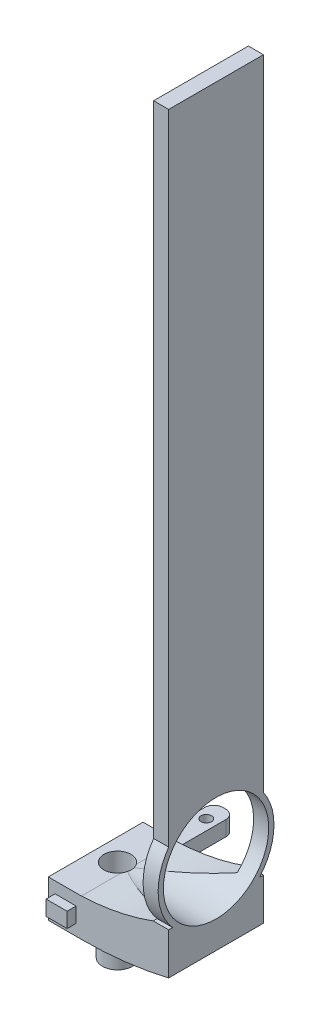
SolidWorks part; units mm, degrees
material "Cast Alloy Steel"
ref_plane "Front Plane" through (0, 0, 0) normal (0, 0, 1) x (1, 0, 0)
ref_plane "Top Plane" through (0, 0, 0) normal (0, 1, 0) x (1, 0, 0)
ref_plane "Right Plane" through (0, 0, 0) normal (1, 0, 0) x (0, 0, -1)
sketch "Sketch1" plane through (0, 0, 0) normal (0, 0, 1) x (1, 0, 0)
  line L0 (0, 0) -> (0, 25.0004)
  line L1 (0, 25.0004) -> (22, 25.0004)
  line L3 (22, 0) -> (0, 0)
  line L4 (0, 25.0004) -> (0, -234) construction
  line L8 (80, 38.7514) -> (80, 6.7987)
  arc A0 (22, 25.0004) -> (80, 38.7514) centre (15.9028, 179.9111) ccw
  arc A1 (22, 0) -> (80, 6.7987) centre (22, 250.8008) ccw
  dimension "D1" = 22
  dimension "D2" = 80
  dimension "D3" = 22
extrude "Boss-Extrude1" add sketch "Sketch1" along normal blind 48
sketch "Sketch2" plane through (0, 0, 48) normal (0, 0, 1) x (1, 0, 0)
  line L0 (0, 0) -> (0, 7.5) construction
  line L1 (0, 25.0004) -> (0, 0) construction
  line L2 (0, 7.5) -> (4.5, 7.5) construction
  line L3 (4.5, 7.5) -> (4.5, 17.5)
  line L4 (4.5, 17.5) -> (18.5, 17.5)
  line L5 (18.5, 17.5) -> (18.5, 7.5)
  line L6 (4.5, 7.5) -> (18.5, 7.5)
  dimension "D1" = 14
  dimension "D2" = 10
  dimension "D3" = 4.5
extrude "Boss-Extrude2" add sketch "Sketch2" along normal blind 50
ref_plane "Plane1" through (0, 0, 24) normal (0, 0, 1) x (1, 0, 0)
sketch "Sketch4" plane through (0, 17.5, 0) normal (0, 1, 0) x (1, 0, 0)
  line L0 (11.5, -48) -> (11.5, -86)
  line L1 (18.5, -48) -> (4.5, -48) construction
hole_wizard "M8x1.0 Tapped Hole1" positions "3DSketch1" profile "Sketch5" tap size "M8x1.0" standard "ANSI Metric"
sketch3d "3DSketch1"
  point P0 (11.5, 17.5, 86)
sketch "Sketch5" plane through (11.5, 17.5, 86) normal (1, 0, 0) x (0, 0, 1)
  line L0 (0, 0) -> (0, 12.103)
  line L1 (0, 12.103) -> (3.5, 10)
  line L2 (3.5, 10) -> (3.5, 0)
  line L5 (3.5, 0) -> (0, 0)
  line L10 (0, 12.103) -> (-3.5, 10) construction
  line L11 (0, -6.35) -> (0, 107.95) construction
  dimension "Tap Drill Dia." = 7
  dimension "Tap Drill Depth" = 10
  dimension "Drill Angle" = 118
cosmetic thread "Hole Thread1" parameters "D1"=10, "D2"=8
fillet "Fillet1" radius 6 2 edges at (4.5, 12.5, 98) (18.5, 12.5, 98)
ref_plane "Plane2" through (80, 0, 0) normal (-1, 0, 0) x (0, 0, 1)
sketch "Sketch7" plane through (80, 0, 0) normal (-1, 0, 0) x (0, 0, 1)
  line L0 (24, 25.0004) -> (24, 60.0004) construction
  line L1 (48, 25.0004) -> (0, 25.0004) construction
  circle A0 centre (24, 60.0004) radius 35
  circle A1 centre (24, 60.0004) radius 38.5
extrude "Boss-Extrude3" add sketch "Sketch7" along normal blind 10
sketch "Sketch8" plane through (80, 0, 0) normal (-1, 0, 0) x (0, 0, 1)
  circle A0 centre (24, 60.0004) radius 35
extrude "Cut-Extrude2" cut sketch "Sketch8" along normal blind 90
sketch "Sketch10" plane through (0, 0, 0) normal (0, -1, 0) x (1, 0, 0)
  line L0 (0, 24) -> (14.5, 24) construction
  line L1 (0, 48) -> (0, 0) construction
  circle A0 centre (14.5, 24) radius 12
  circle A1 centre (14.5, 24) radius 9
extrude "Boss-Extrude4" add sketch "Sketch10" along normal blind 5 and the other way blind 10
sketch "Sketch11" plane through (0, -5, 0) normal (0, -1, 0) x (1, 0, 0)
  circle A0 centre (14.5, 24) radius 10
  circle A1 centre (14.5, 24) radius 9
extrude "Boss-Extrude5" add sketch "Sketch11" along normal blind 25
sketch "Sketch12" plane through (0, 0, 0) normal (0, -1, 0) x (-1, 0, 0)
  circle A0 centre (-14.5, -24) radius 9
extrude "Cut-Extrude3" cut sketch "Sketch12" against normal blind 42
sketch "Sketch13" plane through (0, 0, 48) normal (0, 0, 1) x (1, 0, 0)
  line L0 (0, 25.0004) -> (0, 0)
  line L1 (0, 0) -> (22, 0)
  line L2 (0, 25.0004) -> (22, 25.0004)
  line L3 (69.7299, 34.5249) -> (70, 34.5249)
  line L6 (80, 29.8964) -> (80, 6.7987)
  line L10 (70, 34.5249) -> (80, 34.5249)
  line L11 (80, 29.8964) -> (80, 98.5004) construction
  line L12 (80, 34.5249) -> (80, 29.8964)
  arc A0 (22, 0) -> (80, 6.7987) centre (22, 250.8008) ccw construction
  arc A1 (22, 25.0004) -> (69.7299, 34.5249) centre (15.9028, 179.9111) ccw
  arc A2 (22, 0) -> (80, 6.7987) centre (22, 250.8008) ccw
extrude "Boss-Extrude6" add sketch "Sketch13" along normal blind 7.5
sketch "Sketch14" plane through (0, 0, 0) normal (0, 0, -1) x (-1, 0, 0)
  line L0 (-80, 29.8964) -> (-80, 6.7987)
  line L1 (-22, 0) -> (0, 0)
  line L2 (0, 0) -> (0, 25.0004)
  line L3 (0, 25.0004) -> (-22, 25.0004)
  line L4 (-69.7299, 34.5249) -> (-70, 34.5249)
  line L7 (-70, 34.5249) -> (-80, 34.5249)
  line L8 (-80, 98.5004) -> (-80, 29.8964) construction
  line L9 (-80, 34.5249) -> (-80, 29.8964)
  arc A0 (-80, 6.7987) -> (-22, 0) centre (-22, 250.8008) ccw
  arc A1 (-22, 25.0004) -> (-69.7299, 34.5249) centre (-15.9028, 179.9111) cw
extrude "Boss-Extrude7" add sketch "Sketch14" along normal blind 7.5
mirror "Mirror1" about plane through (0, 0, 24) normal (0, 0, 1) of "Fillet1", "M8x1.0 Tapped Hole1", "Boss-Extrude2"
ref_plane "Plane3" through (0, 0, 61.5) normal (0, 0, 1) x (1, 0, 0)
sketch "Sketch15" plane through (0, 0, 61.5) normal (0, 0, 1) x (1, 0, 0)
  line L1 (4.5, 7.5) -> (18.5, 7.5)
  line L2 (4.5, 7.5) -> (4.5, 17.5)
  line L3 (4.5, 17.5) -> (18.5, 17.5)
  line L4 (18.5, 7.5) -> (18.5, 17.5)
extrude "Cut-Extrude4" cut sketch "Sketch15" along normal blind 101
sketch "Sketch16" plane through (80, 0, 0) normal (1, 0, 0) x (0, 0, -1)
  line L0 (-55.5, 75.2565) -> (-55.5, 506.7987)
  line L1 (-55.5, 506.7987) -> (7.5, 506.7987)
  line L2 (7.5, 506.7987) -> (7.5, 75.2565)
  arc A0 (-55.5, 75.2565) -> (7.5, 75.2565) centre (-24, 60.0004) cw
  circle A1 centre (-24, 60.0004) radius 35 construction
extrude "Boss-Extrude8" add sketch "Sketch16" against normal up to surface (10 mm away) up to face at (70, 65.6377, 24)
